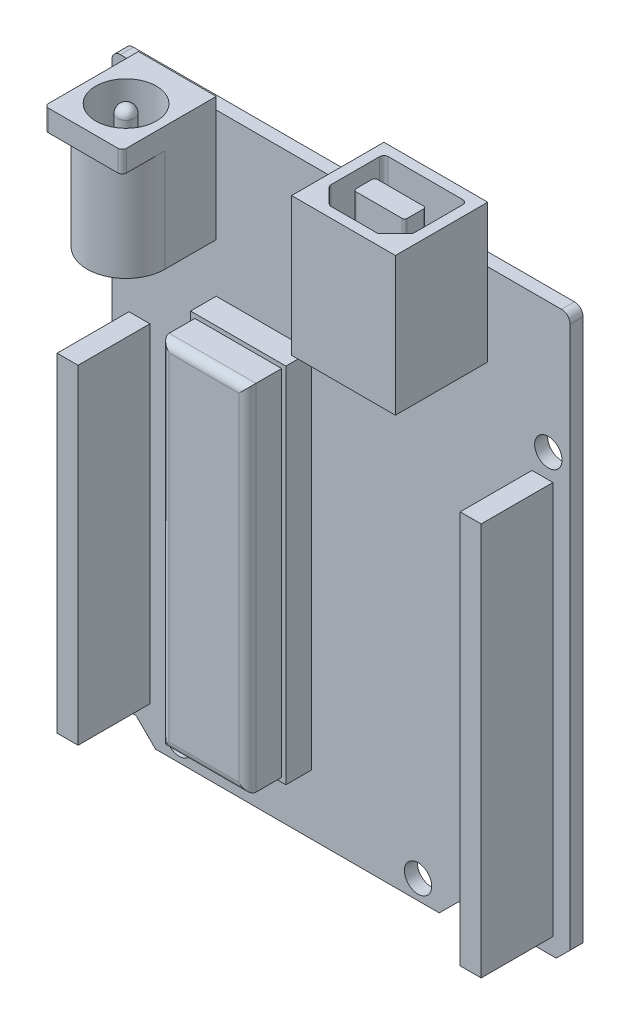
SolidWorks part; units mm, degrees
ref_plane "Plano frontal" through (0, 0, 0) normal (0, 0, 1) x (1, 0, 0)
ref_plane "Plano superior" through (0, 0, 0) normal (0, 1, 0) x (1, 0, 0)
ref_plane "Plano direito" through (0, 0, 0) normal (1, 0, 0) x (0, 0, -1)
sketch "Esboço1" plane through (0, 0, 0) normal (0, 0, 1) x (1, 0, 0)
  line L0 (394.0427, -113.3801) -> (394.0427, -807.3801) construction
  line L1 (25.8, 34.15) -> (-25.8, 34.15)
  line L2 (26.8, 33.15) -> (26.8, -30.2831)
  line L3 (11.5, -34.15) -> (-21.7, -34.15)
  line L4 (-26.8, 33.15) -> (-26.8, -30.89)
  line L5 (-25.8, -31.89) -> (-23.96, -31.89)
  line L6 (-21.7, -34.15) -> (-23.96, -31.89)
  line L7 (11.5, -34.15) -> (13.76, -31.89)
  line L8 (25.1931, -31.89) -> (26.8, -30.2831)
  line L9 (13.76, -31.89) -> (25.1931, -31.89)
  line L11 (-23.6867, 35.5261) -> (-14.5902, 35.5261)
  line L12 (-23.6867, 35.5261) -> (-23.6867, 21.0187)
  line L13 (-23.6867, 21.0187) -> (-14.5902, 21.0187)
  line L14 (-14.5902, 35.5261) -> (-14.5902, 21.0187)
  line L15 (17.1703, 40.6929) -> (5.03, 40.6929)
  line L16 (17.1703, 40.6929) -> (17.1703, 24.5058)
  line L17 (17.1703, 24.5058) -> (5.03, 24.5058)
  line L18 (5.03, 40.6929) -> (5.03, 24.5058)
  circle A0 centre (-24, 18.91) radius 1.6
  circle A1 centre (24.26, 18.91) radius 1.6
  circle A2 centre (-18.92, -31.89) radius 1.6
  circle A3 centre (9.02, -31.89) radius 1.6
  arc A4 (25.8, 34.15) -> (26.8, 33.15) centre (25.8, 33.15) cw
  arc A5 (-25.8, 34.15) -> (-26.8, 33.15) centre (-25.8, 33.15) ccw
  arc A6 (-25.8, -31.89) -> (-26.8, -30.89) centre (-25.8, -30.89) cw
  point P0 (0, 0)
  point P18 (26.8, 34.15)
  point P21 (-26.8, 34.15)
  dimension "D6" = 3.2
  dimension "D7" = 3.2
  dimension "D8" = 3.2
  dimension "D9" = 3.2
  dimension "D15" = 1
  dimension "D2" = 1
  dimension "D1" = 53.6
  dimension "D3" = 0
  dimension "D4" = 17.78
  dimension "D5" = 45.72
  dimension "D10" = 66.04
  dimension "D11" = 50.8
  dimension "D12" = 15.24
  dimension "D13" = 2.54
  dimension "D14" = 0
  dimension "D16" = 5.1
  dimension "D17" = 15.3
  dimension "D18" = 68.3
sketch "Esboço2" plane through (0, 0, 0) normal (0, 0, 1) x (1, 0, 0)
  line L0 (26.8, -30.2831) -> (25.1931, -31.89)
  line L1 (25.1931, -31.89) -> (13.76, -31.89)
  line L2 (26.8, -30.2831) -> (26.8, 33.15)
  line L3 (25.8, 34.15) -> (-25.8, 34.15)
  line L4 (-26.8, -30.89) -> (-26.8, 33.15)
  line L5 (-23.96, -31.89) -> (-21.7, -34.15)
  line L6 (-21.7, -34.15) -> (11.5, -34.15)
  line L7 (11.5, -34.15) -> (13.76, -31.89)
  line L8 (-23.96, -31.89) -> (-25.8, -31.89)
  arc A0 (26.8, 33.15) -> (25.8, 34.15) centre (25.8, 33.15) ccw
  arc A1 (-25.8, 34.15) -> (-26.8, 33.15) centre (-25.8, 33.15) ccw
  arc A2 (-26.8, -30.89) -> (-25.8, -31.89) centre (-25.8, -30.89) ccw
  circle A3 centre (-24, 18.91) radius 1.6
  circle A4 centre (24.26, 18.91) radius 1.6
  circle A5 centre (-18.92, -31.89) radius 1.6
  circle A6 centre (9.02, -31.89) radius 1.6
  point P20 (-26.8, 34.15)
  dimension "D1" = 1
extrude "Ressalto-extrusão1" add sketch "Esboço2" along normal blind 1.52
sketch "Esboço3" plane through (0, 0, 1.52) normal (0, 0, 1) x (1, 0, 0)
  line L1 (-14.5902, 21.0187) -> (-23.6867, 21.0187)
  line L2 (-14.5902, 21.0187) -> (-14.5902, 35.5261)
  line L3 (-14.5902, 35.5261) -> (-23.6867, 35.5261)
  line L4 (-23.6867, 21.0187) -> (-23.6867, 35.5261)
extrude "Ressalto-extrusão2" add sketch "Esboço3" along normal blind 11
sketch "Esboço4" plane through (0, 0, 1.52) normal (0, 0, 1) x (1, 0, 0)
  line L1 (-24.8, -29.89) -> (-22.35, -29.89)
  line L2 (-24.8, -29.89) -> (-24.8, 8.61)
  line L3 (-24.8, 8.61) -> (-22.35, 8.61)
  line L4 (-22.35, -29.89) -> (-22.35, 8.61)
  line L5 (-26.8, 33.15) -> (-26.8, -30.89) construction
  line L6 (-25.8, -31.89) -> (-23.96, -31.89) construction
  line L7 (13.76, -31.89) -> (25.1931, -31.89) construction
  line L8 (22.35, -29.89) -> (24.8, -29.89)
  line L9 (22.35, -29.89) -> (22.35, 16.11)
  line L10 (22.35, 16.11) -> (24.8, 16.11)
  line L11 (24.8, -29.89) -> (24.8, 16.11)
  line L12 (26.8, 33.15) -> (26.8, -30.2831) construction
  dimension "D1" = 38.5
  dimension "D2" = 2.45
  dimension "D3" = 2
  dimension "D4" = 2
  dimension "D5" = 2
  dimension "D6" = 2
  dimension "D7" = 2.45
  dimension "D8" = 46
extrude "Ressalto-extrusão3" add sketch "Esboço4" along normal blind 8.4
sketch "Esboço5" plane through (0, 21.0187, 0) normal (0, -1, 0) x (1, 0, 0)
  line L0 (-19.1384, 12.52) -> (-19.1384, 12.0682) construction
  line L1 (-23.6867, 12.52) -> (-14.5902, 12.52) construction
  line L3 (-14.5902, 7.52) -> (-14.5902, 12.52)
  line L5 (-14.5902, 12.52) -> (-23.6867, 12.52)
  line L6 (-23.6867, 12.52) -> (-23.6867, 7.52)
  arc A0 (-14.5902, 7.52) -> (-23.6867, 7.52) centre (-19.1384, 7.52) ccw
  dimension "D1" = 5
extrude "Corte-extrusão1" cut sketch "Esboço5" against normal blind 12
sketch "Esboço6" plane through (0, 35.5261, 0) normal (0, -1, 0) x (1, 0, 0)
  circle A0 centre (-19.1384, 7.52) radius 3.5482
  circle A1 centre (-19.1384, 7.52) radius 1
  arc A2 (-14.5902, 7.52) -> (-23.6867, 7.52) centre (-19.1384, 7.52) ccw construction
  dimension "D1" = 1
  dimension "D2" = 2
extrude "Corte-extrusão2" cut sketch "Esboço6" along normal blind 12
fillet "Filete1" radius 1 1 edges at (-19.1384, 35.5261, 6.52)
fillet "Filete2" radius 0.5 2 edges at (-23.6867, 34.2724, 12.52) (-14.5902, 34.2724, 12.52)
sketch "Esboço7" plane through (0, 0, 1.52) normal (0, 0, 1) x (1, 0, 0)
  line L1 (17.1703, 40.6929) -> (5.03, 40.6929)
  line L2 (17.1703, 40.6929) -> (17.1703, 24.5058)
  line L3 (17.1703, 24.5058) -> (5.03, 24.5058)
  line L4 (5.03, 40.6929) -> (5.03, 24.5058)
extrude "Ressalto-extrusão4" add sketch "Esboço7" along normal blind 10.8
sketch "Esboço8" plane through (0, 0, 0) normal (0, 0, -1) x (-1, 0, 0)
  line L0 (25.8, 34.15) -> (-25.8, 34.15) construction
  line L3 (0, 34.15) -> (0, -38.2715) construction
sketch "Esboço9" plane through (0, 40.6929, 0) normal (0, 1, 0) x (1, 0, 0)
  line L0 (17.1703, -12.32) -> (5.03, -1.52) construction
  line L1 (17.1703, -12.32) -> (5.03, -12.32) construction
  line L2 (6.73, -2.72) -> (15.4703, -2.72)
  line L3 (6.23, -3.22) -> (6.23, -8.9129)
  line L4 (8.4371, -11.12) -> (13.7632, -11.12)
  line L5 (15.9703, -3.22) -> (15.9703, -8.9129)
  line L6 (6.23, -2.72) -> (15.9703, -11.12) construction
  line L7 (6.23, -11.12) -> (15.9703, -2.72) construction
  line L8 (5.03, -12.32) -> (5.03, -1.52) construction
  line L9 (14.1168, -10.9736) -> (15.8239, -9.2664)
  line L10 (13.8001, -8.17) -> (8.4001, -8.17)
  line L11 (14.1001, -7.87) -> (14.1001, -5.97)
  line L12 (13.8001, -5.67) -> (8.4001, -5.67)
  line L13 (8.1001, -7.87) -> (8.1001, -5.97)
  line L14 (14.1001, -8.17) -> (8.1001, -5.67) construction
  line L15 (14.1001, -5.67) -> (8.1001, -8.17) construction
  line L16 (6.3764, -9.2664) -> (8.0835, -10.9736)
  arc A0 (8.4001, -8.17) -> (8.1001, -7.87) centre (8.4001, -7.87) cw
  arc A1 (8.4001, -5.67) -> (8.1001, -5.97) centre (8.4001, -5.97) ccw
  arc A2 (14.1001, -5.97) -> (13.8001, -5.67) centre (13.8001, -5.97) ccw
  arc A3 (13.8001, -8.17) -> (14.1001, -7.87) centre (13.8001, -7.87) ccw
  arc A4 (6.73, -2.72) -> (6.23, -3.22) centre (6.73, -3.22) ccw
  arc A5 (15.4703, -2.72) -> (15.9703, -3.22) centre (15.4703, -3.22) cw
  arc A6 (6.3764, -9.2664) -> (6.23, -8.9129) centre (6.73, -8.9129) cw
  arc A7 (8.0835, -10.9736) -> (8.4371, -11.12) centre (8.4371, -10.62) ccw
  arc A8 (14.1168, -10.9736) -> (13.7632, -11.12) centre (13.7632, -10.62) cw
  arc A9 (15.8239, -9.2664) -> (15.9703, -8.9129) centre (15.4703, -8.9129) ccw
  point P4 (11.1001, -6.92)
  point P13 (11.1001, -6.92)
  point P42 (6.23, -9.12)
  point P45 (8.23, -11.12)
  point P48 (13.9703, -11.12)
  point P51 (15.9703, -9.12)
  dimension "D5" = 0.3
  dimension "D6" = 0.5
  dimension "D7" = 0.5
  dimension "D1" = 1.2
  dimension "D2" = 1.2
  dimension "D3" = 6
  dimension "D4" = 2.5
extrude "Corte-extrusão3" cut sketch "Esboço9" against normal blind 10
sketch "Esboço10" plane through (0, 0, 1.52) normal (0, 0, 1) x (1, 0, 0)
  line L1 (-3.9426, 14.7819) -> (-14.0935, 14.7819)
  line L2 (-3.9426, 14.7819) -> (-3.9426, -26.6376)
  line L3 (-3.9426, -26.6376) -> (-14.0935, -26.6376)
  line L4 (-14.0935, 14.7819) -> (-14.0935, -26.6376)
extrude "Ressalto-extrusão5" add sketch "Esboço10" along normal blind 7
fillet "Filete3" radius 1 4 edges at (-9.018, 14.7819, 8.52) (-3.9426, -5.9278, 8.52) (-9.018, -26.6376, 8.52) (-14.0935, -5.9278, 8.52)
sketch "Esboço11" plane through (0, 0, 1.52) normal (0, 0, 1) x (1, 0, 0)
  line L1 (-4.9426, -5.9278) -> (-13.0935, -5.9278) construction
  line L2 (-4.9426, -25.6376) -> (-4.9426, 13.7819) construction
  line L3 (-13.0935, 13.7819) -> (-13.0935, -25.6376) construction
  line L4 (-3.9426, -26.6376) -> (-3.9426, 14.7819) construction
  line L5 (-14.5935, -27.1376) -> (-3.4426, -27.1376)
  line L6 (-14.5935, -27.1376) -> (-14.5935, 15.2819)
  line L7 (-14.5935, 15.2819) -> (-3.4426, 15.2819)
  line L8 (-3.4426, -27.1376) -> (-3.4426, 15.2819)
  line L9 (-14.5935, -27.1376) -> (-3.4426, 15.2819) construction
  line L10 (-14.5935, 15.2819) -> (-3.4426, -27.1376) construction
  line L11 (-3.9426, 14.7819) -> (-14.0935, 14.7819) construction
  point P6 (-9.018, -5.9278)
  dimension "D1" = 0.5
  dimension "D2" = 0.5
extrude "Ressalto-extrusão6" add sketch "Esboço11" along normal blind 3
